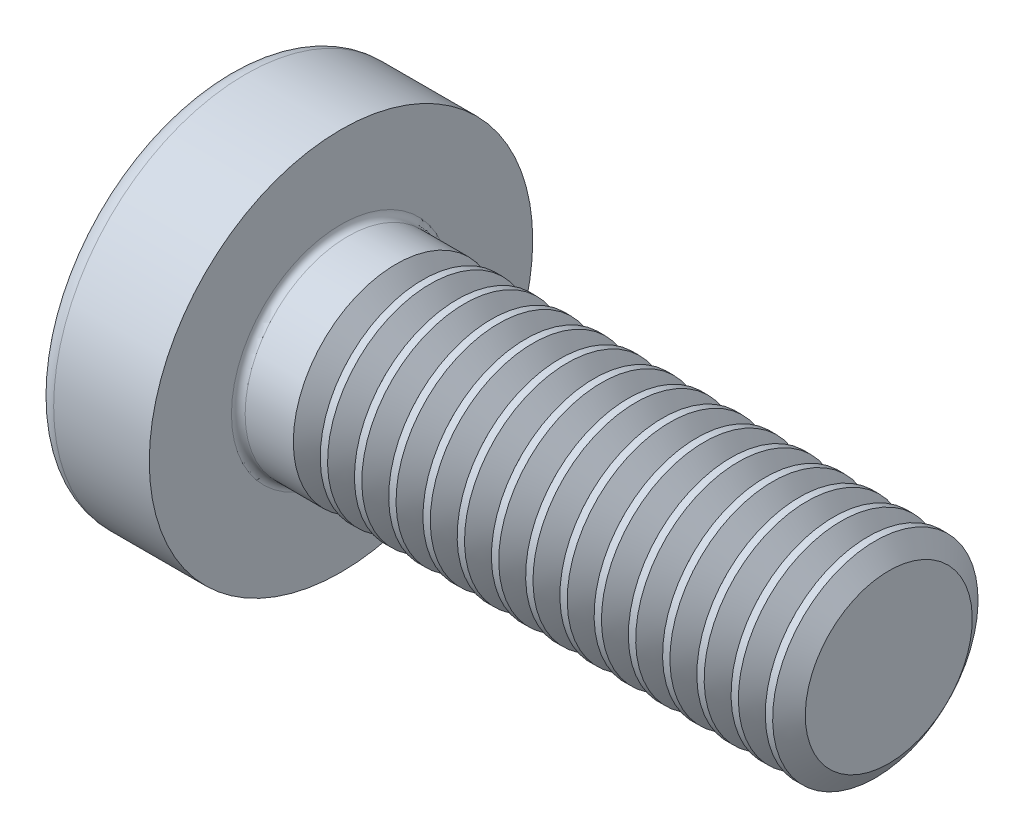
SolidWorks part; units mm, degrees
ref_plane "Plane1" through (0, 0, 0) normal (0, 0, 1) x (1, 0, 0)
ref_plane "Plane2" through (0, 0, 0) normal (0, 1, 0) x (1, 0, 0)
ref_plane "Plane3" through (0, 0, 0) normal (1, 0, 0) x (0, 0, -1)
sketch "BodySke" plane through (0, 0, 0) normal (0, 0, 1) x (1, 0, 0)
  line L0 (2.4, 1.5) -> (2.4, 2.8)
  line L1 (2.65, 6.35) -> (2.65, -3.175) construction
  line L2 (-25.4, 0) -> (127, 0) construction
  line L3 (10.4, 0) -> (0, 0)
  line L4 (2.4, 1.5) -> (10.4, 1.5)
  line L5 (10.4, 1.5) -> (10.4, 0)
  line L6 (1.0035, 2.8) -> (2.4, 2.8)
  line L8 (2.4, 6.35) -> (2.4, -3.175) construction
  arc A0 (0.7754, 2.6744) -> (0, 0) centre (5, 0) ccw
  arc A2 (0.7754, 2.6744) -> (1.0035, 2.8) centre (1.0035, 2.53) cw
  dimension "Head_fillet_rad" = 0.27
  dimension "Head_crown_rad" = 5
  dimension "Head_ht" = 2.4
  dimension "Diameter" = 3
  dimension "Length" = 8
  dimension "Head_dia" = 5.6
  dimension "Advance" = 0.5
  dimension "Thread_nom" = 8
revolve "Base-Revolve" add sketch "BodySke"
cosmetic thread "ThreadCosmetic" [suppressed]
fillet "Fillet1" radius 0.1 1 edges at (2.4, 0, 1.5)
sketch "Sketch3" plane through (0, 0, 0) normal (1, 0, 0) x (0, 0, -1)
  line L0 (0.37, -1.4) -> (-0.37, -1.4)
  line L1 (0.37, -1.4) -> (0.37, 1.4)
  line L2 (-0.37, 1.4) -> (0.37, 1.4)
  line L3 (-0.37, 1.4) -> (-0.37, -1.4)
  dimension "D1" = 1.4
  dimension "Cross_dia" = 2.8
  dimension "D2" = 0.37
  dimension "Cross_width" = 0.74
ref_plane "Plane4" through (1.75, 0, 0) normal (1, 0, 0) x (0, 0, -1)
sketch "Sketch4" plane through (1.75, 0, 0) normal (1, 0, 0) x (0, 0, -1)
  line L0 (0.37, -0.5275) -> (-0.37, -0.5275)
  line L1 (0.37, -0.5275) -> (0.37, 0.5275)
  line L2 (-0.37, 0.5275) -> (0.37, 0.5275)
  line L3 (-0.37, 0.5275) -> (-0.37, -0.5275)
  dimension "D1" = 0.74
  dimension "D2" = 1.055
  dimension "D3" = 0.37
  dimension "D4" = 0.5275
loft "Recess" cut profiles "Sketch3", "Sketch4"
pattern_circular "RecPat" count 2 every 90 about axis through (0, 0, 0) along (1, 0, 0) of "Recess"
sketch "RecCorSke" plane through (0, 0, 0) normal (0, 0, 1) x (1, 0, 0)
  line L0 (-3.175, 0) -> (15.875, 0) construction
  line L1 (-25.4, 0) -> (127, 0) construction
  line L2 (0, 0) -> (0, 0.6784)
  line L3 (0, 0.6784) -> (1.75, 0.556)
  line L4 (1.75, 0.556) -> (1.9307, 0)
  line L5 (1.9307, 0) -> (0, 0)
  dimension "Diameter" = 1.112
  dimension "Depth" = 1.75
  dimension "Draft_angle" = 4
  dimension "Bottom_angle" = 18
revolve "RecessCore" cut sketch "RecCorSke" angle 360 about L0
sketch "ThdSchSke" plane through (0, 0, 0) normal (0, 0, 1) x (1, 0, 0)
  line L0 (3.4, -1.2195) -> (3.2036, -1.5)
  line L1 (3.4, -1.2195) -> (3.5964, -1.5)
  line L2 (3.5964, -1.5) -> (3.5964, -1.875)
  line L3 (-3.175, 0) -> (5.1513, 0) construction
  line L5 (3.5964, -1.875) -> (3.2036, -1.875)
  line L6 (3.2036, -1.875) -> (3.2036, -1.5)
  dimension "Thread_minor" = 2.439
  dimension "Diameter" = 3
  dimension "Start" = 3.4
  dimension "SideAngle" = 55
  dimension "VeeAngle" = 70
  dimension "Overcut" = 3.75
revolve "ThreadSchematic" cut sketch "ThdSchSke" angle 360 about L3
pattern_linear "ThdSchPat" count 15 spacing 0.5 along (1, 0, 0) of "ThreadSchematic"
equation "\"D1@Sketch3\" = \"Cross_dia@Sketch3\" / 2"
equation "\"D2@Sketch3\" = \"Cross_width@Sketch3\" / 2"
equation "\"Depth@RecCorSke\" = \"Cross_depth@Plane4\""
equation "\"D1@Sketch4\" = \"Cross_width@Sketch3\""
equation "\"D2@Sketch4\" = \"Cross_dia@Sketch3\" - 2.0 * \"Cross_depth@Plane4\" * tan(26.5  * 0.017453292)"
equation "\"D3@Sketch4\" = \"D1@Sketch4\" / 2"
equation "\"D4@Sketch4\" = \"D2@Sketch4\" / 2"
equation "\"Thread_length@ThreadCosmetic\" = ((sgn( (\"Length@BodySke\" - \"Advance@BodySke\" * 2.0 ) - \"Thread_nom@BodySke\" )-1)*( (\"Length@BodySke\" - \"Advance@BodySke\" * 2.0 ) - \"Thread_nom@BodySke\" ))/-2+ \"Thread_nom@BodySke\""
equation "\"Thread_minor@ThdSchSke\" = \"Thread_minor@ThreadCosmetic\""
equation "\"Diameter@ThdSchSke\" = \"Diameter@BodySke\""
equation "\"Overcut@ThdSchSke\" = \"Diameter@BodySke\" * 1.25"
equation "\"Start@ThdSchSke\" = \"Head_ht@BodySke\" + \"Length@BodySke\" - \"Thread_length@ThreadCosmetic\"  '---Non-countersunk---"
equation "\"Num_threads@ThdSchPat\" = int( \"Thread_length@ThreadCosmetic\" / \"Advance@BodySke\" + 0.999 )  + 1"
equation "\"Advance@ThdSchPat\" = \"Thread_length@ThreadCosmetic\" /  (\"Num_threads@ThdSchPat\" - 1) 'relax it"
